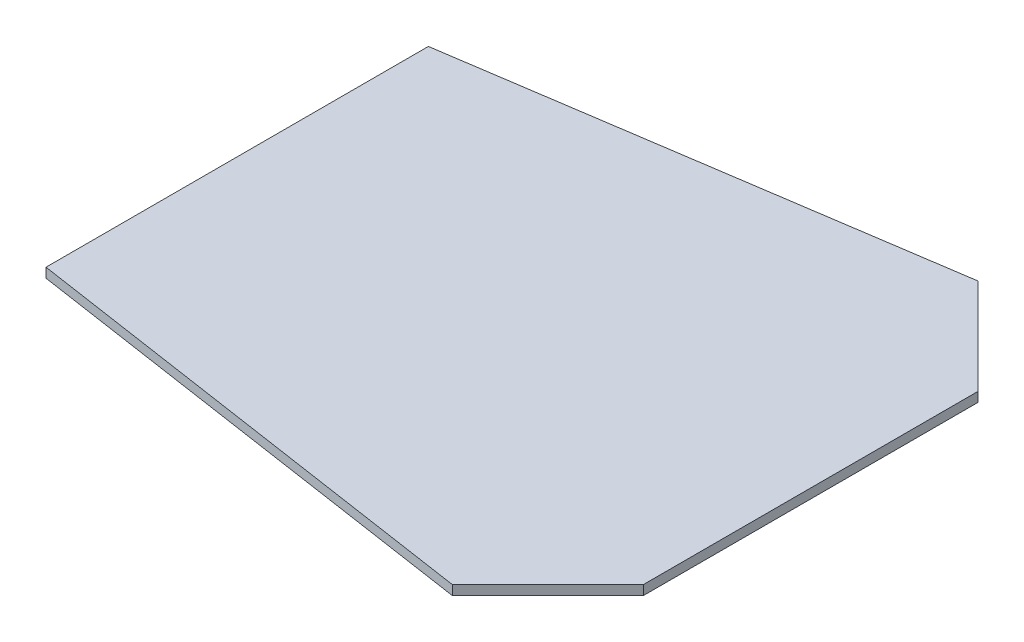
SolidWorks part; units mm, degrees
ref_plane "Front Plane" through (0, 0, 0) normal (0, 0, 1) x (1, 0, 0)
ref_plane "Top Plane" through (0, 0, 0) normal (0, 1, 0) x (1, 0, 0)
ref_plane "Right Plane" through (0, 0, 0) normal (1, 0, 0) x (0, 0, -1)
sketch "Sketch1" plane through (0, 0, 0) normal (0, 1, 0) x (1, 0, 0)
  line L0 (-59.8851, 437.9662) -> (-59.8851, 37.9662)
  line L2 (540.1149, 62.9662) -> (540.1149, 412.9662)
  line L5 (440.1149, 512.9662) -> (-59.8851, 437.9662)
  line L7 (-59.8851, 237.9662) -> (540.1149, 237.9662) construction
  line L8 (440.1149, -37.0338) -> (-59.8851, 37.9662)
  line L10 (440.1149, 512.9662) -> (540.1149, 412.9662)
  line L11 (440.1149, -37.0338) -> (540.1149, 62.9662)
  dimension "D1" = 400
  dimension "D2" = 350
  dimension "D3" = 600
  dimension "D4" = 100
  dimension "D5" = 100
  dimension "D6" = 100
  dimension "D7" = 100
  dimension "D8" = 75
extrude "Boss-Extrude1" add sketch "Sketch1" along normal blind 10
ref_plane "Plane1" through (0, 5, 0) normal (0, 1, 0) x (1, 0, 0)
sketch "Sketch3" plane through (0, 5, 0) normal (0, 1, 0) x (1, 0, 0)
  line L0 (-59.8851, 237.9662) -> (560.1437, 237.9662) construction
  line L1 (-59.8851, 437.9662) -> (-59.8851, 37.9662) construction
